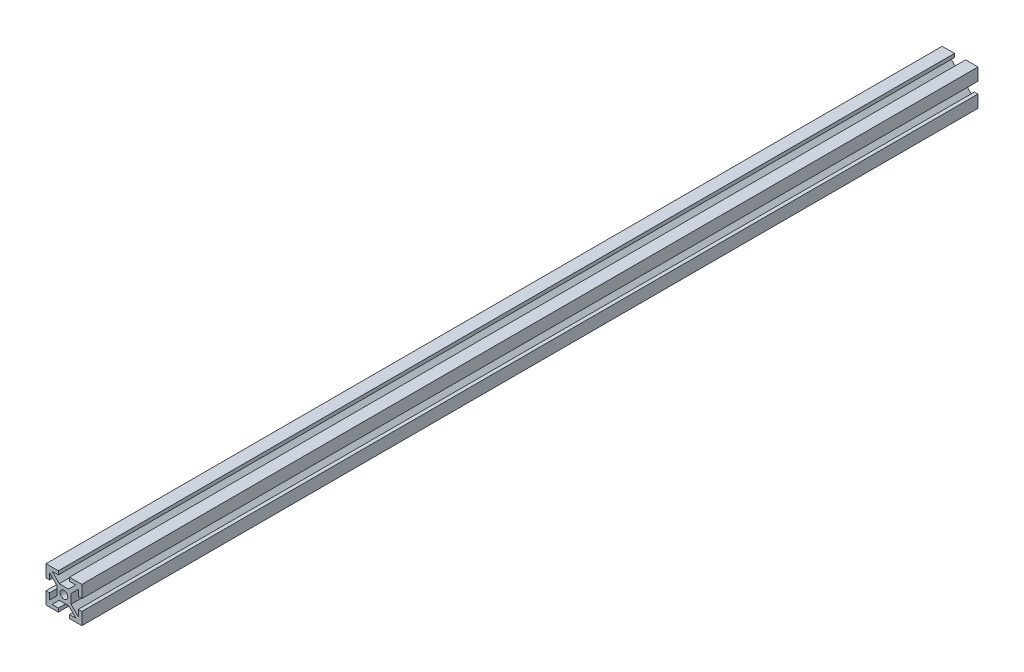
SolidWorks part; units mm, degrees
ref_plane "Plan de face" through (0, 0, 0) normal (0, 0, 1) x (1, 0, 0)
ref_plane "Plan de dessus" through (0, 0, 0) normal (0, 1, 0) x (1, 0, 0)
ref_plane "Plan de droite" through (0, 0, 0) normal (1, 0, 0) x (0, 0, -1)
sketch "Esquisse1" plane through (0, 0, 0) normal (0, 0, 1) x (1, 0, 0)
  line L0 (20, 13.1) -> (18, 13.1)
  line L1 (0, 0) -> (6.9, 0)
  line L2 (0, 0) -> (0, 6.9)
  line L3 (0, 20) -> (6.9, 20)
  line L4 (20, 0) -> (20, 6.9)
  line L5 (18, 13.1) -> (18, 16.5858)
  line L6 (0, 0) -> (20, 20) construction
  line L7 (14, 12.5858) -> (14, 10)
  line L8 (14, 12.5858) -> (18, 16.5858)
  line L9 (13.1, 20) -> (13.1, 18)
  line L10 (13.1, 18) -> (16.5858, 18)
  line L11 (12.5858, 14) -> (16.5858, 18)
  line L12 (12.5858, 14) -> (10, 14)
  line L13 (14, 7.4142) -> (14, 10)
  line L14 (14, 7.4142) -> (18, 3.4142)
  line L15 (18, 6.9) -> (18, 3.4142)
  line L16 (20, 6.9) -> (18, 6.9)
  line L17 (13.1, 2) -> (16.5858, 2)
  line L18 (12.5858, 6) -> (16.5858, 2)
  line L19 (13.1, 0) -> (13.1, 2)
  line L20 (12.5858, 6) -> (10, 6)
  line L21 (7.4142, 6) -> (10, 6)
  line L22 (7.4142, 6) -> (3.4142, 2)
  line L23 (6.9, 2) -> (3.4142, 2)
  line L24 (6.9, 0) -> (6.9, 2)
  line L25 (2, 6.9) -> (2, 3.4142)
  line L26 (6, 7.4142) -> (2, 3.4142)
  line L27 (0, 6.9) -> (2, 6.9)
  line L28 (6, 7.4142) -> (6, 10)
  line L29 (6, 12.5858) -> (6, 10)
  line L30 (6, 12.5858) -> (2, 16.5858)
  line L31 (2, 13.1) -> (2, 16.5858)
  line L32 (0, 13.1) -> (2, 13.1)
  line L33 (6.9, 18) -> (3.4142, 18)
  line L34 (7.4142, 14) -> (3.4142, 18)
  line L35 (6.9, 20) -> (6.9, 18)
  line L36 (7.4142, 14) -> (10, 14)
  line L37 (20, 13.1) -> (20, 20)
  line L38 (13.1, 20) -> (20, 20)
  line L39 (0, 13.1) -> (0, 20)
  line L40 (13.1, 0) -> (20, 0)
  circle A0 centre (10, 10) radius 2.15
  point P51 (10, 10)
  dimension "D2" = 4.3
  dimension "D1" = 20
  dimension "D3" = 2
  dimension "D4" = 6.2
  dimension "D5" = 6
  dimension "D6" = 2
  dimension "D7" = 4
extrude "Boss.-Extru.1" add sketch "Esquisse1" along normal blind 500
